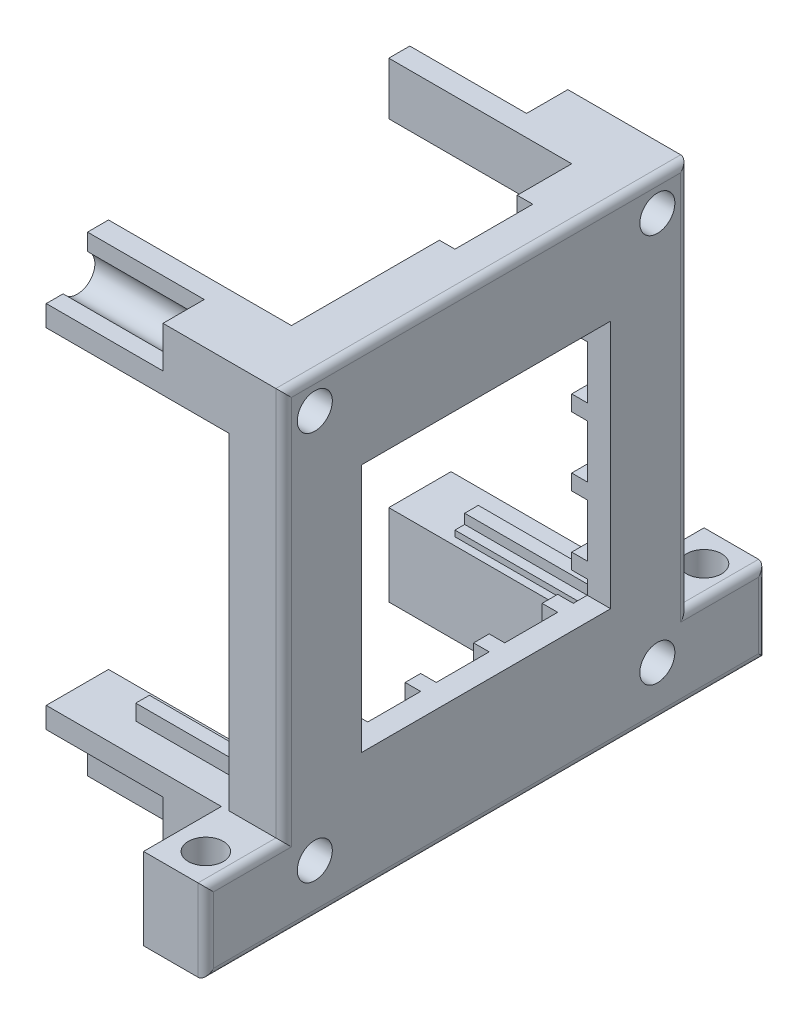
SolidWorks part; units mm, degrees
ref_plane "Front Plane" through (0, 0, 0) normal (0, 0, 1) x (1, 0, 0)
ref_plane "Top Plane" through (0, 0, 0) normal (0, 1, 0) x (1, 0, 0)
ref_plane "Right Plane" through (0, 0, 0) normal (1, 0, 0) x (0, 0, -1)
sketch "Sketch1" plane through (0, 0, 0) normal (1, 0, 0) x (0, 0, -1)
  line L1 (16, -16) -> (-16, -16)
  line L2 (16, -16) -> (16, 16)
  line L3 (16, 16) -> (-16, 16)
  line L4 (-16, -16) -> (-16, 16)
  line L5 (16, -16) -> (-16, 16) construction
  line L6 (16, 16) -> (-16, -16) construction
  line L7 (21, -21) -> (-21, -21) construction
  line L8 (21, -21) -> (21, 21) construction
  line L9 (21, 21) -> (-21, 21) construction
  line L10 (-21, -21) -> (-21, 21) construction
  line L11 (21, -21) -> (-21, 21) construction
  line L12 (21, 21) -> (-21, -21) construction
  line L13 (26, -29) -> (-26, -29)
  line L14 (26, -29) -> (26, 29)
  line L15 (26, 29) -> (-26, 29)
  line L16 (-26, -29) -> (-26, 29)
  line L17 (26, -29) -> (-26, 29) construction
  line L18 (26, 29) -> (-26, -29) construction
  point P0 (0, 0)
  point P6 (0, 0)
  point P11 (0, 0)
  dimension "D1" = 42
  dimension "D2" = 5
  dimension "D3" = 5
  dimension "D4" = 8
extrude "Boss-Extrude1" add sketch "Sketch1" against normal blind 3
sketch "Sketch2" plane through (-3, 0, 0) normal (-1, 0, 0) x (0, 0, 1)
  line L0 (26, 29) -> (26, -29) construction
  line L1 (21, -21) -> (-21, -21)
  line L2 (21, -21) -> (21, 21)
  line L3 (21, 21) -> (-21, 21)
  line L4 (-21, -21) -> (-21, 21)
  line L5 (21, -21) -> (-21, 21) construction
  line L6 (21, 21) -> (-21, -21) construction
  line L7 (26, -29) -> (-26, -29) construction
  line L8 (-26, -29) -> (-26, 29) construction
  line L9 (-26, 29) -> (26, 29) construction
  line L10 (26, 29) -> (26, -29)
  line L11 (26, -29) -> (-26, -29)
  line L12 (-26, -29) -> (-26, 29)
  line L13 (-26, 29) -> (26, 29)
  point P0 (0, 0)
  dimension "D1" = 42
extrude "Boss-Extrude2" add sketch "Sketch2" along normal blind 4
sketch "Sketch3" plane through (-7, 0, 0) normal (-1, 0, 0) x (0, 0, 1)
  line L0 (21, 21) -> (-21, 21) construction
  line L1 (-26, 29) -> (-18, 29)
  line L2 (-26, 29) -> (-26, 21)
  line L3 (-26, 21) -> (-18, 21)
  line L4 (-18, 29) -> (-18, 21)
  dimension "D1" = 8
extrude "Boss-Extrude3" add sketch "Sketch3" along normal blind 23.5
sketch "Sketch4" plane through (0, 0, 0) normal (1, 0, 0) x (0, 0, -1)
  line L0 (26, 29) -> (-26, 29) construction
  line L1 (26, -29) -> (26, 29) construction
  circle A0 centre (22, 25) radius 2.25
  dimension "D1" = 4.5
  dimension "D2" = 4
  dimension "D3" = 4
extrude "Cut-Extrude1" cut sketch "Sketch4" against normal through all
sketch "Sketch5" plane through (-30.5, 0, 0) normal (-1, 0, 0) x (0, 0, 1)
  line L1 (-20.7, 23.7) -> (-26, 23.7)
  line L2 (-20.7, 23.7) -> (-20.7, 29)
  line L3 (-20.7, 29) -> (-26, 29)
  line L4 (-26, 23.7) -> (-26, 29)
  dimension "D1" = 5.3
extrude "Cut-Extrude2" cut sketch "Sketch5" against normal blind 15
mirror "Mirror1" about plane through (0, 0, 0) normal (0, 1, 0) of "Cut-Extrude2", "Boss-Extrude3", "Cut-Extrude1"
mirror "Mirror2" about plane through (0, 0, 0) normal (0, 0, 1) of "Mirror1", "Boss-Extrude3", "Cut-Extrude1", "Cut-Extrude2"
sketch "Sketch6" plane through (-3, 0, 0) normal (-1, 0, 0) x (0, 0, 1)
  line L0 (21, 21) -> (-21, 21) construction
  line L1 (-14.2, 21) -> (-12.2, 21)
  line L2 (-14.2, 21) -> (-14.2, 20.25)
  line L3 (-14.2, 20.25) -> (-12.2, 20.25)
  line L4 (-12.2, 21) -> (-12.2, 20.25)
  line L5 (18, 21) -> (-18, 21) construction
  line L6 (-5.4, 21) -> (-3.4, 21)
  line L7 (-5.4, 21) -> (-5.4, 20.25)
  line L8 (-5.4, 20.25) -> (-3.4, 20.25)
  line L9 (-3.4, 21) -> (-3.4, 20.25)
  line L10 (21, -21) -> (21, 21) construction
  line L11 (3.4, 21) -> (5.4, 21)
  line L12 (3.4, 21) -> (3.4, 20.25)
  line L13 (3.4, 20.25) -> (5.4, 20.25)
  line L14 (5.4, 21) -> (5.4, 20.25)
  line L15 (12.2, 21) -> (14.2, 21)
  line L16 (12.2, 21) -> (12.2, 20.25)
  line L17 (12.2, 20.25) -> (14.2, 20.25)
  line L18 (14.2, 21) -> (14.2, 20.25)
  line L19 (21, 14.2) -> (20.25, 14.2)
  line L20 (21, 14.2) -> (21, 12.2)
  line L21 (21, 12.2) -> (20.25, 12.2)
  line L22 (20.25, 14.2) -> (20.25, 12.2)
  line L23 (21, -21) -> (21, 21) construction
  line L24 (21, 5.4) -> (20.25, 5.4)
  line L25 (21, 5.4) -> (21, 3.4)
  line L26 (21, 3.4) -> (20.25, 3.4)
  line L27 (20.25, 5.4) -> (20.25, 3.4)
  line L28 (-21, 21) -> (-21, -21) construction
  line L29 (-21, 14.2) -> (-20.25, 14.2)
  line L30 (-21, 14.2) -> (-21, 12.2)
  line L31 (-21, 12.2) -> (-20.25, 12.2)
  line L32 (-20.25, 14.2) -> (-20.25, 12.2)
  line L33 (-21, 21) -> (-21, -21) construction
  line L34 (-21, 5.4) -> (-20.25, 5.4)
  line L35 (-21, 5.4) -> (-21, 3.4)
  line L36 (-21, 3.4) -> (-20.25, 3.4)
  line L37 (-20.25, 5.4) -> (-20.25, 3.4)
  line L38 (0, 0) -> (0, 21) construction
  line L39 (-21, 21) -> (-14.2, 21) construction
  line L40 (-12.2, 21) -> (-5.4, 21) construction
  line L41 (-3.4, 21) -> (3.4, 21) construction
  line L42 (5.4, 21) -> (12.2, 21) construction
  line L43 (14.2, 21) -> (21, 21) construction
  line L44 (21, 21) -> (21, 14.2) construction
  line L45 (21, 12.2) -> (21, 5.4) construction
  point P51 (0, 21)
  dimension "D1" = 0.75
  dimension "D2" = 2
extrude "Boss-Extrude4" add sketch "Sketch6" along normal up to surface (4 mm away) up to face at (-7, 0, -23.5)
sketch "Sketch7" plane through (-3, 0, 0) normal (-1, 0, 0) x (0, 0, 1)
  line L0 (-16, -16) -> (-16, 16) construction
  line L1 (-20.25, 3.4) -> (-16, 3.4)
  line L2 (-20.25, 3.4) -> (-20.25, 5.4)
  line L3 (-20.25, 5.4) -> (-16, 5.4)
  line L4 (-16, 3.4) -> (-16, 5.4)
  line L5 (-16, 16) -> (16, 16) construction
  line L6 (-20.25, 12.2) -> (-16, 12.2)
  line L7 (-20.25, 12.2) -> (-20.25, 14.2)
  line L8 (-20.25, 14.2) -> (-16, 14.2)
  line L9 (-16, 12.2) -> (-16, 14.2)
  line L10 (-14.2, 20.25) -> (-12.2, 20.25)
  line L11 (-14.2, 20.25) -> (-14.2, 16)
  line L12 (-14.2, 16) -> (-12.2, 16)
  line L13 (-12.2, 20.25) -> (-12.2, 16)
  line L14 (16, 16) -> (16, -16) construction
  line L15 (-5.4, 20.25) -> (-3.4, 20.25)
  line L16 (-5.4, 20.25) -> (-5.4, 16)
  line L17 (-5.4, 16) -> (-3.4, 16)
  line L18 (-3.4, 20.25) -> (-3.4, 16)
  line L19 (3.4, 20.25) -> (5.4, 20.25)
  line L20 (3.4, 20.25) -> (3.4, 16)
  line L21 (3.4, 16) -> (5.4, 16)
  line L22 (5.4, 20.25) -> (5.4, 16)
  line L23 (12.2, 20.25) -> (14.2, 20.25)
  line L24 (12.2, 20.25) -> (12.2, 16)
  line L25 (12.2, 16) -> (14.2, 16)
  line L26 (14.2, 20.25) -> (14.2, 16)
  line L27 (20.25, 14.2) -> (16, 14.2)
  line L28 (20.25, 14.2) -> (20.25, 12.2)
  line L29 (20.25, 12.2) -> (16, 12.2)
  line L30 (16, 14.2) -> (16, 12.2)
  line L31 (21, 3.4) -> (20.25, 3.4) construction
  line L32 (20.25, 5.4) -> (16, 5.4)
  line L33 (20.25, 5.4) -> (20.25, 3.4)
  line L34 (20.25, 3.4) -> (16, 3.4)
  line L35 (16, 5.4) -> (16, 3.4)
  line L36 (20.25, 12.2) -> (21, 12.2) construction
  line L37 (14.2, 21) -> (14.2, 20.25) construction
  line L38 (5.4, 21) -> (5.4, 20.25) construction
  line L39 (-3.4, 21) -> (-3.4, 20.25) construction
  line L40 (-12.2, 20.25) -> (-12.2, 21) construction
  line L41 (-21, 14.2) -> (-20.25, 14.2) construction
  line L42 (-20.25, 5.4) -> (-21, 5.4) construction
extrude "Boss-Extrude5" add sketch "Sketch7" along normal blind 2
mirror "Mirror3" about plane through (0, 0, 0) normal (0, 1, 0) of "Boss-Extrude5", "Boss-Extrude4"
sketch "Sketch8" plane through (-30.5, 0, 0) normal (-1, 0, 0) x (0, 0, 1)
  line L0 (-21, 21) -> (-21, 14.2) construction
  line L1 (-21, 20.25) -> (21, 20.25)
  line L2 (-21, 20.25) -> (-21, 22.25)
  line L3 (-21, 22.25) -> (21, 22.25)
  line L4 (21, 20.25) -> (21, 22.25)
  line L5 (-3.4, 20.25) -> (-5.4, 20.25) construction
  line L6 (21, 14.2) -> (21, 21) construction
  dimension "D1" = 2
extrude "Cut-Extrude3" cut sketch "Sketch8" against normal up to surface (25.5 mm away) up to face at (-5, 18.125, -13.2)
sketch "Sketch9" plane through (-3, 0, 0) normal (-1, 0, 0) x (0, 0, 1)
  line L0 (-22, -21) -> (-22, -19)
  line L2 (-22, -19) -> (-20.25, -19)
  line L3 (-20.25, -19) -> (-20.25, -20.25)
  line L4 (-20.25, -20.25) -> (-19, -20.25)
  line L5 (-19, -20.25) -> (-19, -21)
  line L6 (-18, -21) -> (-14.2, -21) construction
  line L7 (-19, -21) -> (-22, -21)
  line L8 (-20.25, -14.2) -> (-20.25, -12.2) construction
  line L9 (-12.2, -20.25) -> (-14.2, -20.25) construction
  line L10 (-21, -14.2) -> (-21, -21) construction
  dimension "D1" = 2
  dimension "D2" = 3
  dimension "D3" = 1
extrude "Boss-Extrude6" add sketch "Sketch9" along normal blind 20
mirror "Mirror4" about plane through (0, 0, 0) normal (0, 0, 1) of "Boss-Extrude6"
sketch "Sketch10" plane through (0, -29, 0) normal (0, -1, 0) x (1, 0, 0)
  line L0 (0, 28) -> (-8, 36) construction
  line L1 (0, 26) -> (-8, 26)
  line L2 (0, 26) -> (0, 36)
  line L3 (0, 36) -> (-8, 36)
  line L4 (-8, 26) -> (-8, 36)
  circle A0 centre (-4, 32) radius 2.25
  dimension "D1" = 4.5
  dimension "D2" = 10
  dimension "D3" = 8
  dimension "D4" = 8
extrude "Boss-Extrude7" add sketch "Sketch10" against normal up to surface (8 mm away) up to face at (-14.1, -21, 19.84)
mirror "Mirror5" about plane through (0, 0, 0) normal (0, 0, 1) of "Boss-Extrude7"
sketch "Sketch11" plane through (-7, 0, 0) normal (-1, 0, 0) x (0, 0, 1)
  line L0 (-18, 22.25) -> (18, 22.25) construction
  line L1 (-11, 22.25) -> (-1, 22.25)
  line L2 (-11, 22.25) -> (-11, 30.25)
  line L3 (-11, 30.25) -> (-1, 30.25)
  line L4 (-1, 22.25) -> (-1, 30.25)
  line L5 (-18, 22.25) -> (-18, 29) construction
  dimension "D1" = 10
  dimension "D2" = 8
  dimension "D3" = 7
extrude "Cut-Extrude4" cut sketch "Sketch11" against normal blind 2
sketch "Sketch12" plane through (0, -29, 0) normal (0, -1, 0) x (1, 0, 0)
  line L16 (-15.5, 20.7) -> (-30.5, 20.7)
  line L17 (-30.5, 20.7) -> (-30.5, 18)
  line L18 (-30.5, 18) -> (-7, 18)
  line L19 (-7, 18) -> (-7, -18)
  line L20 (-7, -18) -> (-30.5, -18)
  line L21 (-30.5, -18) -> (-30.5, -20.7)
  line L22 (-30.5, -20.7) -> (-15.5, -20.7)
  line L23 (-15.5, -20.7) -> (-15.5, -26)
  line L24 (-15.5, -26) -> (-8, -26)
  line L25 (-8, -26) -> (-8, -36)
  line L26 (-8, -36) -> (0, -36)
  line L27 (0, -36) -> (0, 36)
  line L28 (0, 36) -> (-8, 36)
  line L29 (-8, 36) -> (-8, 26)
  line L30 (-8, 26) -> (-15.5, 26)
  line L31 (-15.5, 26) -> (-15.5, 20.7)
  line L32 (-15.5, 20.7) -> (-30.5, 20.7)
  line L33 (-30.5, 20.7) -> (-30.5, 18)
  line L34 (-30.5, 18) -> (-7, 18)
  line L35 (-7, 18) -> (-7, -18)
  line L36 (-7, -18) -> (-30.5, -18)
  line L37 (-30.5, -18) -> (-30.5, -20.7)
  line L38 (-30.5, -20.7) -> (-15.5, -20.7)
  line L39 (-15.5, -20.7) -> (-15.5, -26)
  line L40 (-15.5, -26) -> (-8, -26)
  line L41 (-8, -26) -> (-8, -36)
  line L42 (-8, -36) -> (0, -36)
  line L43 (0, -36) -> (0, 36)
  line L44 (0, 36) -> (-8, 36)
  line L45 (-8, 36) -> (-8, 26)
  line L46 (-8, 26) -> (-15.5, 26)
  line L47 (-15.5, 26) -> (-15.5, 20.7)
  dimension "D1" = 0
extrude "Boss-Extrude8" add sketch "Sketch12" along normal blind 2.5
fillet "Fillet1" radius 1 8 edges at (0, 29, 0) (0, 4, 26) (0, -21, 31) (0, -26.25, 36) (0, 4, -26) (0, -26.25, -36) (0, -21, -31) (0, -31.5, 0)
